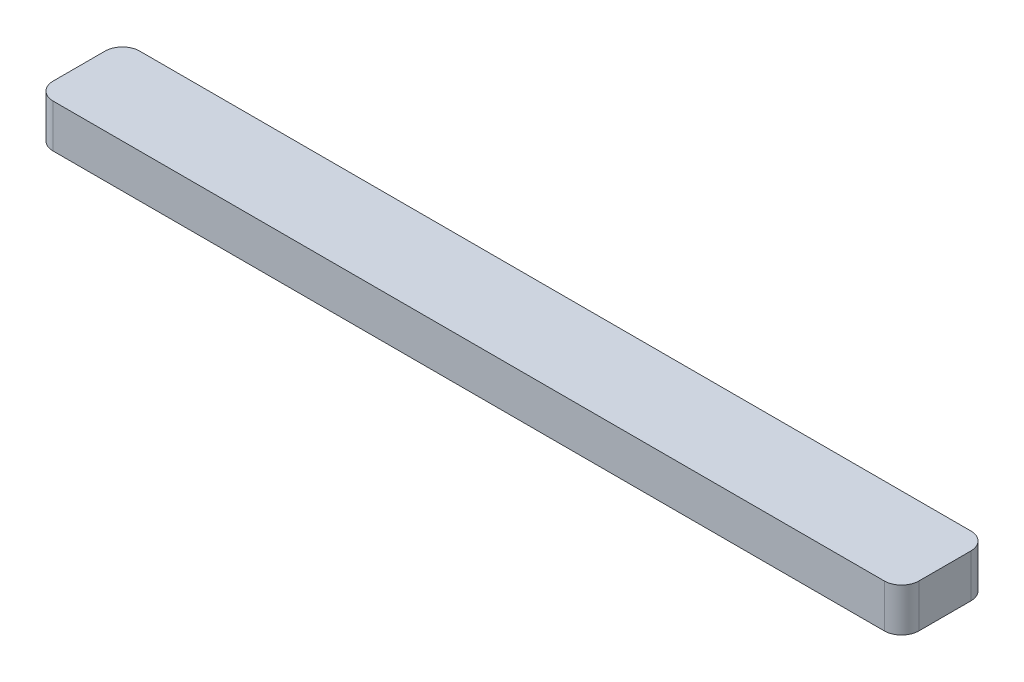
SolidWorks part; units mm, degrees
ref_plane "Plano frontal" through (0, 0, 0) normal (0, 0, 1) x (1, 0, 0)
ref_plane "Plano superior" through (0, 0, 0) normal (0, 1, 0) x (1, 0, 0)
ref_plane "Plano direito" through (0, 0, 0) normal (1, 0, 0) x (0, 0, -1)
sketch "Esboço1" plane through (0, 0, 0) normal (0, 1, 0) x (1, 0, 0)
  line L1 (-48, 5) -> (48, 5)
  line L2 (-50, 3) -> (-50, -3)
  line L3 (-48, -5) -> (48, -5)
  line L4 (50, 3) -> (50, -3)
  line L5 (-50, 5) -> (50, -5) construction
  line L6 (-50, -5) -> (50, 5) construction
  arc A0 (50, 3) -> (48, 5) centre (48, 3) ccw
  arc A1 (50, -3) -> (48, -5) centre (48, -3) cw
  arc A2 (-48, -5) -> (-50, -3) centre (-48, -3) cw
  arc A3 (-50, 3) -> (-48, 5) centre (-48, 3) cw
  point P0 (0, 0)
  dimension "D3" = 2
  dimension "D1" = 10
  dimension "D2" = 100
extrude "Ressalto-extrusão1" add sketch "Esboço1" along normal blind 5
